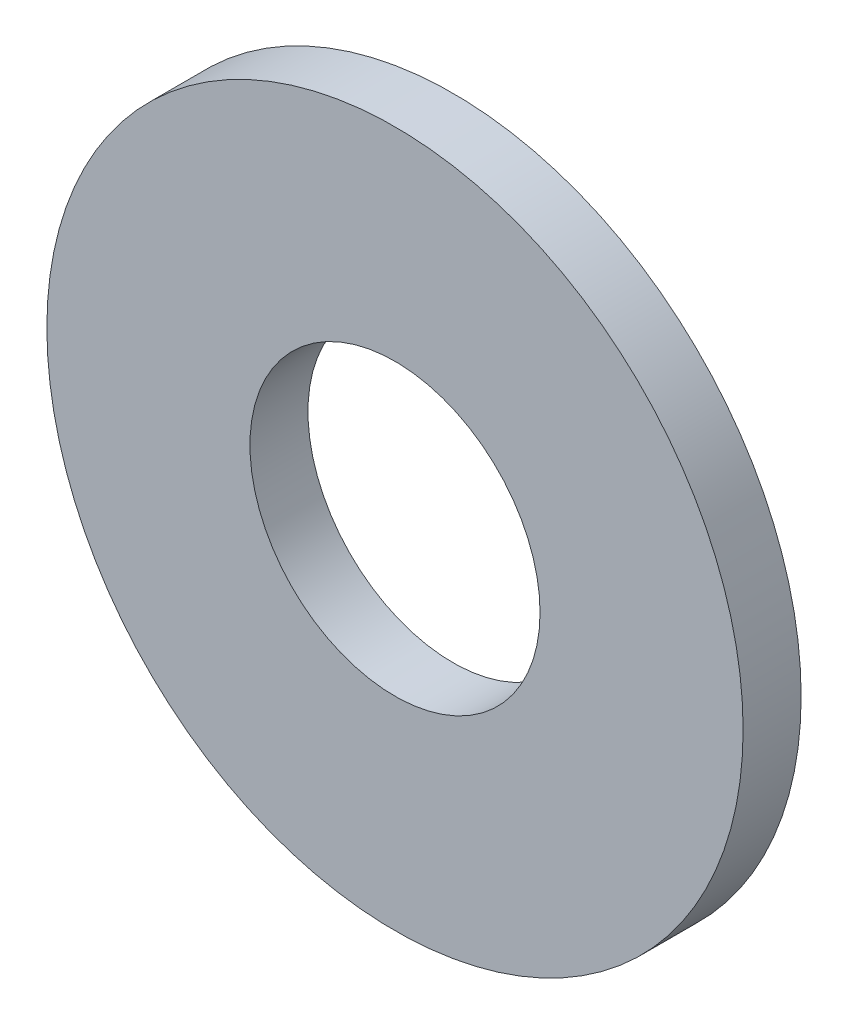
SolidWorks part; units mm, degrees
ref_plane "Alzado" through (0, 0, 0) normal (0, 0, 1) x (1, 0, 0)
ref_plane "Planta" through (0, 0, 0) normal (0, 1, 0) x (1, 0, 0)
ref_plane "Vista lateral" through (0, 0, 0) normal (1, 0, 0) x (0, 0, -1)
sketch3d "Sk_Anillo"
  line L0 (-425.1, 65, 58) -> (-425.1, 65, 60)
sweep "Anillo" add path "Sk_Anillo" circular profile diameter 24 parameters "D3"=24
sketch3d "Sk_Taladro"
  line L0 (-425.1, 65, 58) -> (-425.1, 65, 60)
sweep "Taladro" cut path "Sk_Taladro" circular profile diameter 10 parameters "D3"=10
